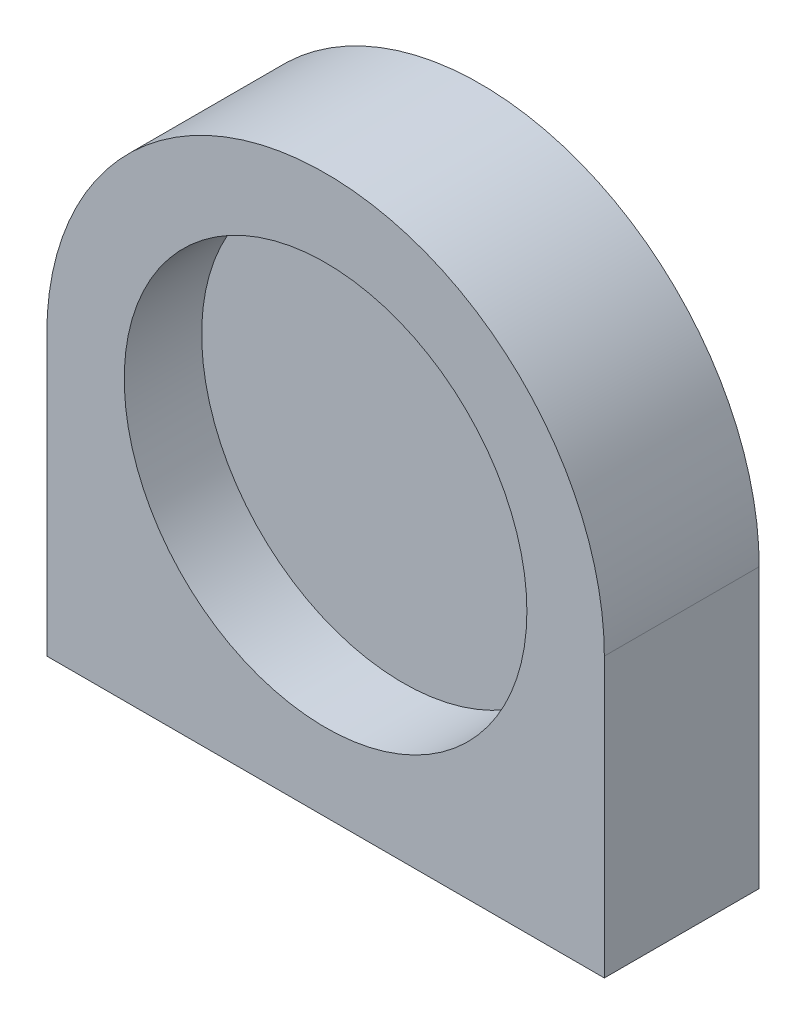
SolidWorks part; units mm, degrees
ref_plane "前视基准面" through (0, 0, 0) normal (0, 0, 1) x (1, 0, 0)
ref_plane "上视基准面" through (0, 0, 0) normal (0, 1, 0) x (1, 0, 0)
ref_plane "右视基准面" through (0, 0, 0) normal (1, 0, 0) x (0, 0, -1)
sketch "草图1" plane through (0, 0, 0) normal (0, 0, 1) x (1, 0, 0)
  line L0 (-9, 0) -> (-9, -9)
  line L1 (-9, -9) -> (9, -9)
  line L2 (9, -9) -> (9, 0)
  circle A0 centre (0, 0) radius 6.5
  arc A1 (9, 0) -> (-9, 0) centre (0, 0) ccw
extrude "凸台-拉伸1" add sketch "草图1" along normal blind 2.5
sketch "草图2" plane through (0, 0, 0) normal (0, 0, -1) x (-1, 0, 0)
  line L3 (-9, 0) -> (-9, -9)
  line L4 (-9, -9) -> (9, -9)
  line L5 (9, -9) -> (9, 0)
  line L6 (-9, 0) -> (-9, -9)
  line L7 (-9, -9) -> (9, -9)
  line L8 (9, -9) -> (9, 0)
  arc A1 (9, 0) -> (-9, 0) centre (0, 0) ccw
  arc A2 (9, 0) -> (-9, 0) centre (0, 0) ccw
  dimension "D1" = 0
extrude "凸台-拉伸2" add sketch "草图2" along normal blind 2.5
